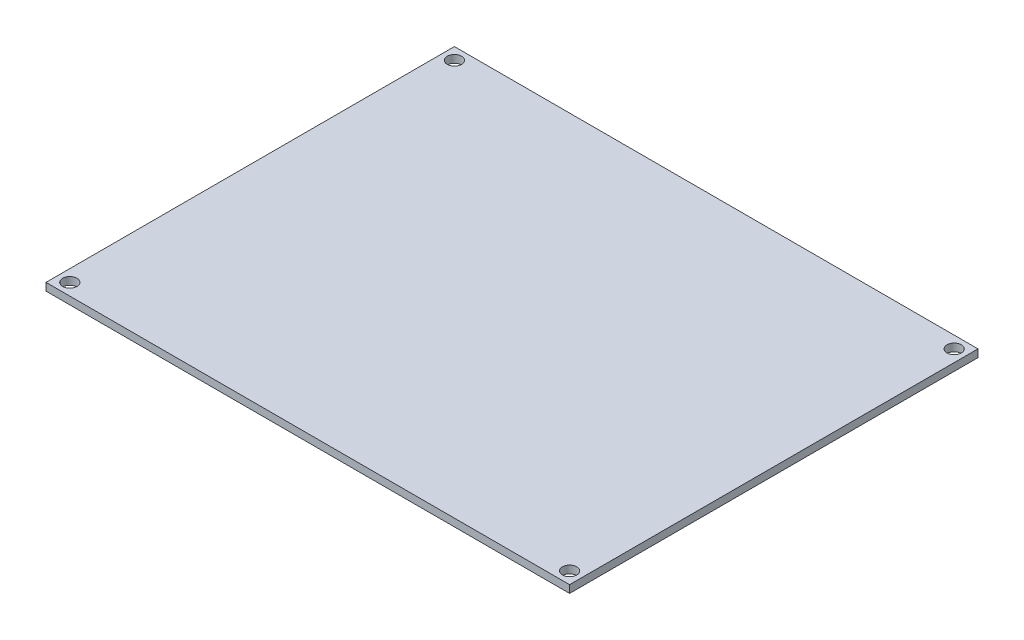
SolidWorks part; units mm, degrees
ref_plane "Front Plane" through (0, 0, 0) normal (0, 0, 1) x (1, 0, 0)
ref_plane "Top Plane" through (0, 0, 0) normal (0, 1, 0) x (1, 0, 0)
ref_plane "Right Plane" through (0, 0, 0) normal (1, 0, 0) x (0, 0, -1)
sketch "Sketch1" plane through (0, 0, 0) normal (0, 1, 0) x (1, 0, 0)
  line L0 (0, -55) -> (0, 55) construction
  line L1 (-55, -42.9) -> (55, -42.9)
  line L2 (-55, -42.9) -> (-55, 42.9)
  line L3 (-55, 42.9) -> (55, 42.9)
  line L4 (55, -42.9) -> (55, 42.9)
  line L5 (-55, -42.9) -> (55, 42.9) construction
  line L6 (-55, 42.9) -> (55, -42.9) construction
  line L7 (-55, 0) -> (55, 0) construction
  circle A0 centre (-52.5, 40.4) radius 1.5
  circle A1 centre (52.5, 40.4) radius 1.5
  circle A2 centre (52.5, -40.4) radius 1.5
  circle A3 centre (-52.5, -40.4) radius 1.5
  point P0 (0, 0)
  dimension "D3" = 3
  dimension "D1" = 110
  dimension "D2" = 85.8
  dimension "D4" = 2.5
  dimension "D5" = 2.5
extrude "Boss-Extrude1" add sketch "Sketch1" along normal blind 1.6
